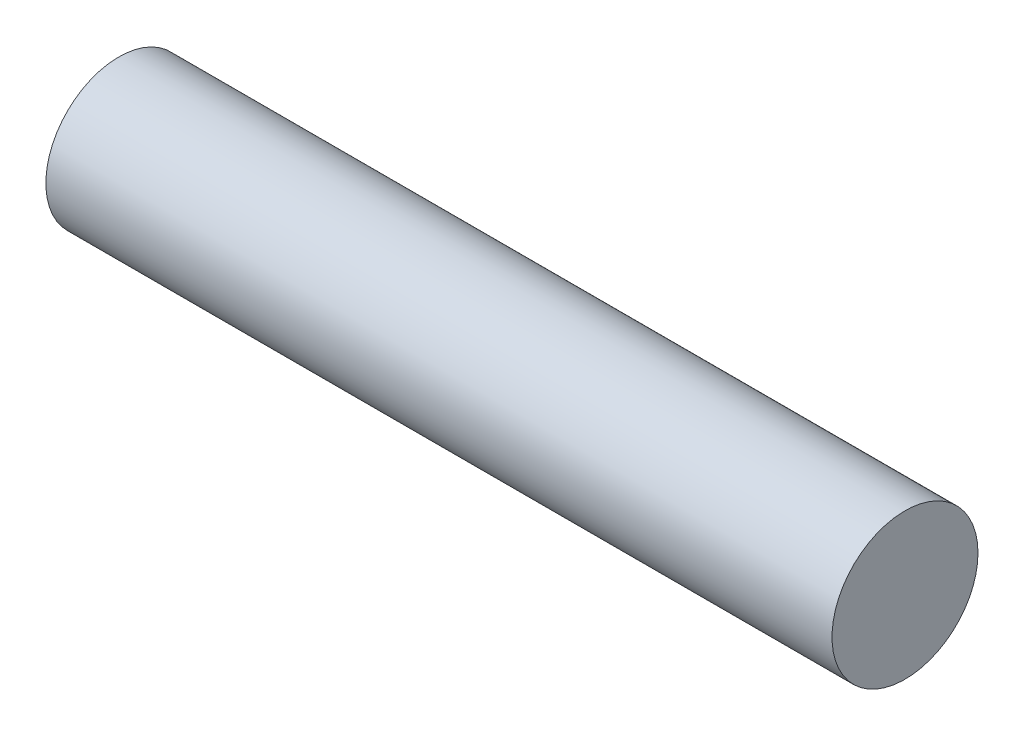
SolidWorks part; units mm, degrees
ref_plane "Plan de face" through (0, 0, 0) normal (0, 0, 1) x (1, 0, 0)
ref_plane "Plan de dessus" through (0, 0, 0) normal (0, 1, 0) x (1, 0, 0)
ref_plane "Plan de droite" through (0, 0, 0) normal (1, 0, 0) x (0, 0, -1)
sketch "Esquisse1" plane through (0, 0, 0) normal (1, 0, 0) x (0, 0, -1)
  circle A0 centre (0, 0) radius 0.65
  dimension "D1" = 1.3
extrude "Extrusion1" add sketch "Esquisse1" along normal blind 7
